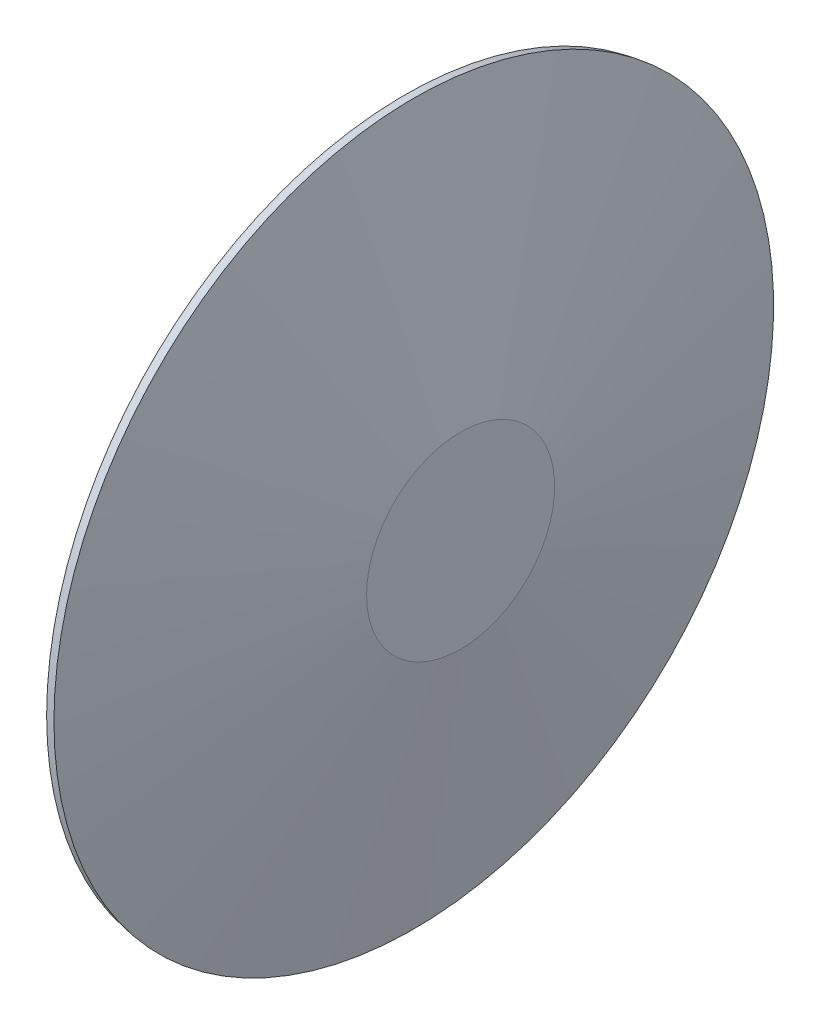
SolidWorks part; units mm, degrees
ref_plane "前视基准面" through (0, 0, 0) normal (0, 0, 1) x (1, 0, 0)
ref_plane "上视基准面" through (0, 0, 0) normal (0, 1, 0) x (1, 0, 0)
ref_plane "右视基准面" through (0, 0, 0) normal (1, 0, 0) x (0, 0, -1)
other "Configuration Table"
sketch "草图1" plane through (0, 0, 0) normal (0, 0, 1) x (1, 0, 0)
  line L0 (0, 0) -> (0, 20.9115)
  line L1 (0, 20.9115) -> (-10.4189, 80)
  line L2 (-10.4189, 80) -> (-12.3885, 79.6527)
  line L3 (-12.3885, 79.6527) -> (-2, 20.7366)
  line L4 (-2, 20.7366) -> (-2, 0)
  line L5 (-2, 0) -> (0, 0)
  dimension "D1" = 2
  dimension "D2" = 80
  dimension "D3" = 60
  dimension "D4" = 2
  dimension "D5" = 10
revolve "旋转1" add sketch "草图1" angle 360 about L5
sketch "草图2" plane through (-2, 0, 0) normal (-1, 0, 0) x (0, 0, 1)
  circle A0 centre (0, 0) radius 7.5
  dimension "D1" = 15
extrude "凸台-拉伸1" add sketch "草图2" along normal blind 50
